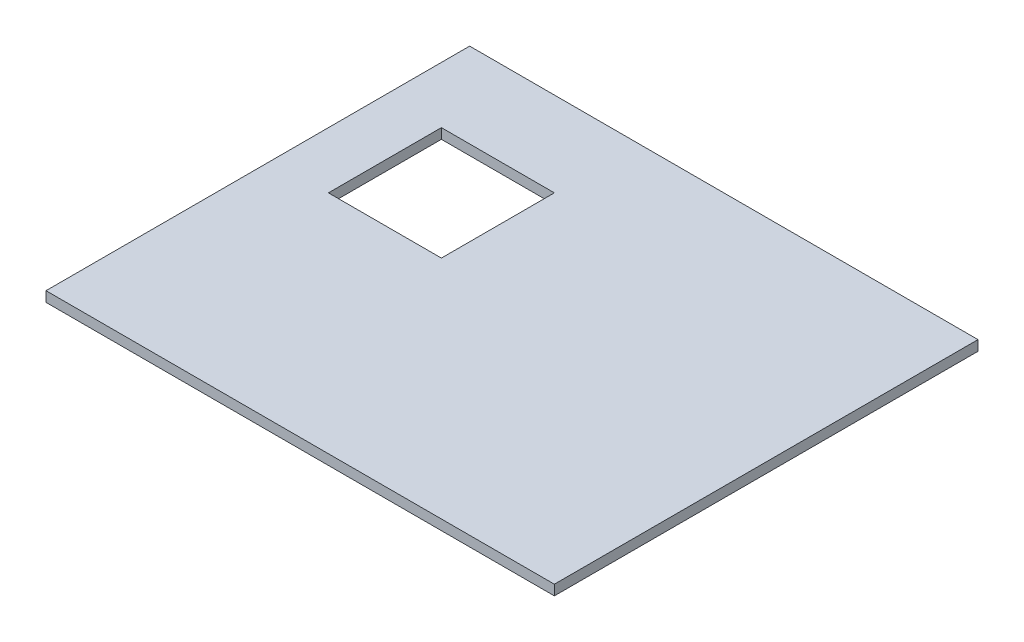
SolidWorks part; units mm, degrees
ref_plane "Front Plane" through (0, 0, 0) normal (0, 0, 1) x (1, 0, 0)
ref_plane "Top Plane" through (0, 0, 0) normal (0, 1, 0) x (1, 0, 0)
ref_plane "Right Plane" through (0, 0, 0) normal (1, 0, 0) x (0, 0, -1)
sketch "Sketch1" plane through (0, 0, 0) normal (0, 1, 0) x (1, 0, 0)
  line L1 (-457.2, -381) -> (457.2, -381)
  line L2 (-457.2, -381) -> (-457.2, 381)
  line L3 (-457.2, 381) -> (457.2, 381)
  line L4 (457.2, -381) -> (457.2, 381)
  line L5 (-457.2, -381) -> (457.2, 381) construction
  line L6 (-457.2, 381) -> (457.2, -381) construction
  line L7 (-355.6, 228.6) -> (-152.4, 228.6)
  line L8 (-355.6, 228.6) -> (-355.6, 25.4)
  line L9 (-355.6, 25.4) -> (-152.4, 25.4)
  line L10 (-152.4, 228.6) -> (-152.4, 25.4)
  line L11 (-355.6, 228.6) -> (-152.4, 25.4) construction
  line L12 (-355.6, 25.4) -> (-152.4, 228.6) construction
  point P0 (0, 0)
  point P6 (-254, 127)
  dimension "D1" = 762
  dimension "D2" = 914.4
  dimension "D3" = 203.2
  dimension "D4" = 254
extrude "Boss-Extrude1" add sketch "Sketch1" along normal blind 18.2562
